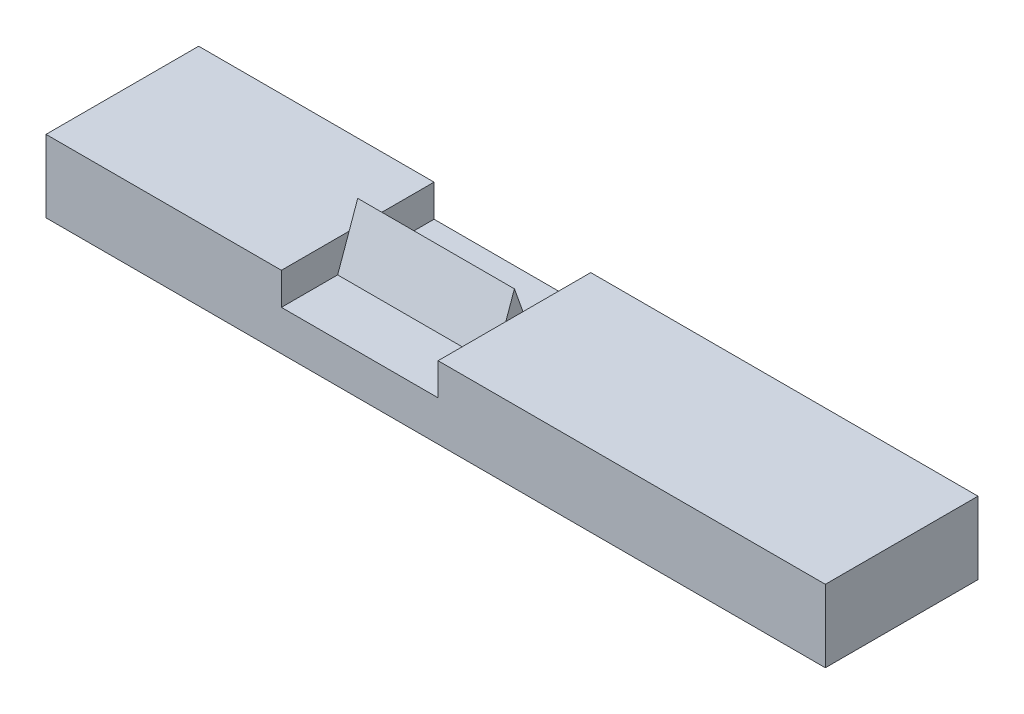
SolidWorks part; units mm, degrees
ref_plane "Front Plane" through (0, 0, 0) normal (0, 0, 1) x (1, 0, 0)
ref_plane "Top Plane" through (0, 0, 0) normal (0, 1, 0) x (1, 0, 0)
ref_plane "Right Plane" through (0, 0, 0) normal (1, 0, 0) x (0, 0, -1)
sketch "Sketch1" plane through (0, 0, 0) normal (0, 1, 0) x (1, 0, 0)
  line L1 (-48.5, -9.5) -> (48.5, -9.5)
  line L2 (-48.5, -9.5) -> (-48.5, 9.5)
  line L3 (-48.5, 9.5) -> (48.5, 9.5)
  line L4 (48.5, -9.5) -> (48.5, 9.5)
  line L5 (-48.5, -9.5) -> (48.5, 9.5) construction
  line L6 (-48.5, 9.5) -> (48.5, -9.5) construction
  point P0 (0, 0)
  dimension "D1" = 19
  dimension "D2" = 97
extrude "Boss-Extrude1" add sketch "Sketch1" against normal blind 10
sketch "Sketch4" plane through (0, 0, 0) normal (0, 1, 0) x (1, 0, 0)
  line L0 (48.5, 9.5) -> (-48.5, 9.5) construction
  line L1 (-19.2, -9.5) -> (0.3, -9.5)
  line L2 (-19.2, -9.5) -> (-19.2, 9.5)
  line L3 (-19.2, 9.5) -> (0.3, 9.5)
  line L4 (0.3, -9.5) -> (0.3, 9.5)
  line L5 (-19.2, -9.5) -> (0.3, 9.5) construction
  line L6 (-19.2, 9.5) -> (0.3, -9.5) construction
  line L7 (-48.5, 9.5) -> (-48.5, -9.5) construction
  point P0 (-9.45, 0)
  dimension "D1" = 19.5
  dimension "D2" = 29.3
extrude "Cut-Extrude1" cut sketch "Sketch4" against normal blind 5
sketch "Sketch5" plane through (0.3, 0, 0) normal (-1, 0, 0) x (0, 0, 1)
  line L0 (9.5, -5) -> (-9.5, -5) construction
  line L1 (-2.5, -5) -> (0, 2)
  line L2 (0, 2) -> (2.5, -5)
  line L3 (2.5, -5) -> (-2.5, -5)
  line L4 (9.5, 0) -> (-9.5, 0) construction
  point P10 (0, 0)
  dimension "D1" = 7
  dimension "D2" = 7
  dimension "D3" = 2
extrude "Boss-Extrude2" add sketch "Sketch5" along normal blind 45.5 and the other way blind 29.5
sketch "Sketch6" plane through (0, 0, 0) normal (0, 1, 0) x (1, 0, 0)
  line L0 (-19.2, 9.5) -> (-48.5, 9.5) construction
  line L1 (-45.5, 9.5) -> (-19.2, 9.5)
  line L2 (-45.5, 9.5) -> (-45.5, -9.5)
  line L3 (-45.5, -9.5) -> (-19.2, -9.5)
  line L4 (-19.2, 9.5) -> (-19.2, -9.5)
  line L5 (0.3, -9.5) -> (48.5, -9.5) construction
  line L6 (0.3, 9.5) -> (45.5, 9.5)
  line L7 (0.3, 9.5) -> (0.3, -9.5)
  line L8 (0.3, -9.5) -> (45.5, -9.5)
  line L9 (45.5, 9.5) -> (45.5, -9.5)
  line L10 (-48.5, 9.5) -> (-48.5, -9.5) construction
  line L11 (48.5, -9.5) -> (48.5, 9.5) construction
  dimension "D1" = 3
  dimension "D2" = 3
extrude "Cut-Extrude2" cut sketch "Sketch6" along normal blind 2
sketch "Sketch7" plane through (0, 0, 0) normal (0, 1, 0) x (1, 0, 0)
  line L1 (-48.5, 9.5) -> (-19.2, 9.5)
  line L2 (-48.5, 9.5) -> (-48.5, -9.5)
  line L3 (-48.5, -9.5) -> (-19.2, -9.5)
  line L4 (-19.2, 9.5) -> (-19.2, -9.5)
  line L5 (0.3, 9.5) -> (48.5, 9.5)
  line L6 (0.3, 9.5) -> (0.3, -9.5)
  line L7 (0.3, -9.5) -> (48.5, -9.5)
  line L8 (48.5, 9.5) -> (48.5, -9.5)
extrude "Cut-Extrude3" cut sketch "Sketch7" against normal blind 1
